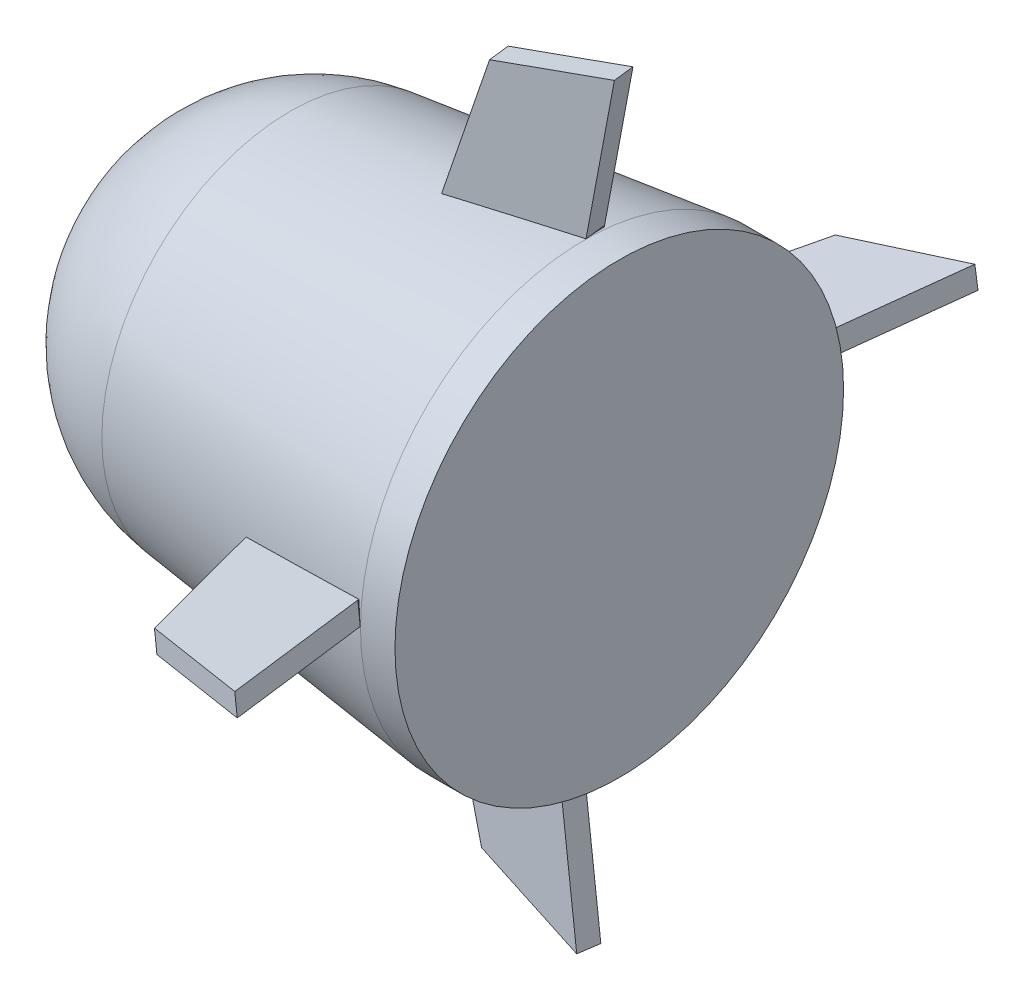
SolidWorks part; units mm, degrees
material "7075-T6 (SN)"
ref_plane "Front Plane" through (0, 0, 0) normal (0, 0, 1) x (1, 0, 0)
ref_plane "Top Plane" through (0, 0, 0) normal (0, 1, 0) x (1, 0, 0)
ref_plane "Right Plane" through (0, 0, 0) normal (1, 0, 0) x (0, 0, -1)
sketch "Sketch1" plane through (0, 0, 0) normal (0, 0, 1) x (1, 0, 0)
  line L1 (68.3553, -5.5711) -> (68.3553, 36.0939)
  line L2 (68.3553, 36.0939) -> (13.6561, 29.4289)
  line L4 (-16.6447, -5.5711) -> (-16.6447, -5.3701)
  line L5 (-16.6447, -5.5711) -> (68.3553, -5.5711)
  arc A0 (13.6561, 29.4289) -> (-16.6447, -5.3701) centre (17.7549, -4.7315) ccw
  dimension "D1" = 85
  dimension "D2" = 41.665
  dimension "D3" = 35
revolve "Revolve1" add sketch "Sketch1" angle 360 about L5
ref_plane "Plane1" through (-4.6714, -38.3379, 0) normal (-0.121, -0.9927, 0) x (-0.9927, 0.121, 0)
sketch "Sketch2" plane through (-4.6714, -38.3379, 0) normal (-0.121, -0.9927, 0) x (-0.9927, 0.121, 0)
  line L0 (0, 0) -> (-73.5668, 0)
  line L1 (-73.5668, 0) -> (-49.7405, 3.134)
  line L2 (-49.7405, 3.134) -> (-49.1838, -1.0985)
  line L3 (-49.1838, -1.0985) -> (-73.0101, -4.2325)
  line L4 (-73.0101, -4.2325) -> (-73.5668, 0)
  ellipse E0 centre (-68.5273, 0) end of major axis (-68.5273, -41.665) minor radius 5.0395 construction
  dimension "D1" = 7.493
ref_plane "Plane2" through (0.6894, -0.084, -5.2796) normal (0.1295, -0.0158, -0.9915) x (0.9842, -0.1199, 0.1304)
sketch "Sketch3" plane through (0.6894, -0.084, -5.2796) normal (0.1295, -0.0158, -0.9915) x (0.9842, -0.1199, 0.1304)
  line L0 (48.907, 38.6214) -> (59.4163, 62.0482)
  line L1 (59.4163, 62.0482) -> (80.5363, 65.0377)
  line L2 (80.5363, 65.0377) -> (72.9385, 38.6214)
  line L3 (72.9385, 38.6214) -> (48.907, 38.6214)
extrude "Boss-Extrude1" add sketch "Sketch3" along normal blind 4 separate body
ref_plane "Plane3" through (-4.6714, -38.3379, 0) normal (0.121, 0.9927, 0) x (0.9927, -0.121, 0)
sketch "Sketch12" plane through (-4.6714, -38.3379, 0) normal (0.121, 0.9927, 0) x (0.9927, -0.121, 0)
  line L0 (49.1838, -1.0985) -> (73.0101, -4.2325)
  line L1 (73.0101, -4.2325) -> (73.5317, -0.2667)
  line L2 (73.5317, -0.2667) -> (49.7054, 2.8673)
  line L3 (49.7054, 2.8673) -> (73.5317, -0.2667) construction
  line L4 (49.7054, 2.8673) -> (49.1838, -1.0985)
extrude "Boss-Extrude5" add sketch "Sketch12" along normal blind 0.5 contours L4 L0 L1 L2
pattern_circular "CirPattern27" count 2 over 360 about axis through (0, -5.5711, 0) along (1, 0, 0) of "Boss-Extrude1", "Boss-Extrude5"
pattern_circular "CirPattern28" count 2 over 270 about axis through (0, -5.5711, 0) along (1, 0, 0) of "Boss-Extrude1", "Boss-Extrude5"
ref_plane "Plane4" through (-3.9926, 0.4865, -32.7632) normal (-0.121, 0.0147, -0.9925) x (-0.9927, -0.002, 0.1209)
sketch "Sketch14" plane through (-3.9926, 0.4865, -32.7632) normal (-0.121, 0.0147, -0.9925) x (-0.9927, -0.002, 0.1209)
  line L0 (0, 0) -> (-72.8525, -1.0289)
  ellipse E0 centre (-67.8424, -5.5832) end of major axis (-67.8502, 36.0817) minor radius 5.0395 construction
mirror "Mirror5" about plane through (0, 0, 0) normal (0, 0, 1) of "CirPattern28", "Boss-Extrude1", "Boss-Extrude5"
ref_plane "Plane5" through (1.2072, -0.1471, -9.2454) normal (0.1295, -0.0158, -0.9915) x (-0.9916, -0.0021, -0.1294)
sketch "Sketch19" plane through (1.2072, -0.1471, -9.2454) normal (0.1295, -0.0158, -0.9915) x (-0.9916, -0.0021, -0.1294)
  line L0 (-67.6792, -47.2353) -> (-71.9959, -74.3814)
  line L1 (-71.9959, -74.3814) -> (-48.207, -72.1348)
  line L2 (-48.207, -72.1348) -> (-43.8273, -44.3021)
  line L3 (-43.8273, -44.3021) -> (-67.6792, -47.2353)
extrude "Cut-Extrude1" cut sketch "Sketch19" along normal blind 7.5 contours L3 L0 L1 L2
ref_plane "Plane8" through (0.6894, -0.084, -5.2796) normal (-0.1295, 0.0158, 0.9915) x (0.9916, 0.0021, 0.1294)
sketch "Sketch25" plane through (0.6894, -0.084, -5.2796) normal (-0.1295, 0.0158, 0.9915) x (0.9916, 0.0021, 0.1294)
  line L0 (50.8912, -68.6997) -> (71.9959, -74.3814)
  line L1 (71.9959, -74.3814) -> (51.3986, -68.8364) construction
  line L2 (71.9959, -74.3814) -> (67.7459, -47.0271)
  line L3 (67.7459, -47.0271) -> (43.8273, -44.3021)
  line L4 (43.8273, -44.3021) -> (50.8912, -68.6997)
  ellipse E0 centre (2180.0534, -5.7378) end of major axis (4472.8952, -5.9139) minor radius 106.5738 (41.4575, 32.8548) -> (58.4264, 34.8346) ccw construction
extrude "Cut-Extrude5" cut sketch "Sketch25" along normal blind 7.5
sketch "Sketch26" plane through (0.6894, -0.084, -5.2796) normal (-0.1295, 0.0158, 0.9915) x (0.9916, 0.0021, 0.1294)
  line L0 (43.8273, -44.3021) -> (43.3255, -44.2404)
  line L1 (43.8273, -44.3021) -> (67.6792, -47.2353) construction
  line L2 (43.8292, -44.2867) -> (43.8273, -44.3021) construction
  line L3 (-4.714, -38.3327) -> (67.6792, -47.2353) construction
  line L4 (43.3255, -44.2404) -> (50.9975, -68.787)
  line L5 (50.9975, -68.787) -> (51.3986, -68.8364)
  line L6 (51.3986, -68.8364) -> (43.8273, -44.3021)
ref_plane "Plane9" through (27.3012, 8.5546, 3.4286) normal (-0.9475, -0.2969, -0.119) x (-0.1138, -0.0346, 0.9929)
sketch "Sketch27" plane through (27.3012, 8.5546, 3.4286) normal (-0.9475, -0.2969, -0.119) x (-0.1138, -0.0346, 0.9929)
  line L0 (-1.0471, -81.1001) -> (-2.4019, -55.4599)
  line L1 (-1.0471, -81.1001) -> (-2.4019, -55.4599) construction
  line L2 (-6.2768, 17.8706) -> (-4.3585, -18.4326) construction
  line L3 (-2.4019, -55.4599) -> (-6.4014, -55.575)
  line L4 (-9.5869, 4.708) -> (-9.0373, -5.6921) construction
  line L5 (-6.4014, -55.575) -> (-5.0415, -81.3112)
  line L6 (-5.0415, -81.3112) -> (-3.5339, -81.2315)
  line L7 (-3.5339, -81.2315) -> (-1.0471, -81.1001)
  ellipse E0 centre (-6.0553, -19.455) end of major axis (-45.7202, -18.1357) minor radius 36.1199 (-6.4014, -55.575) -> (-4.6545, -55.5638) ccw construction
extrude "Cut-Extrude8" cut sketch "Sketch27" along normal blind 7.5 contours L7 L0 L3 L5 L6
ref_plane "Plane11" through (-13.6857, -51.3056, -0.9707) normal (-0.2577, -0.9661, -0.0183) x (-0.9662, 0.2576, 0.0048)
sketch "Sketch28" plane through (-13.6857, -51.3056, -0.9707) normal (-0.2577, -0.9661, -0.0183) x (-0.9662, 0.2576, 0.0048)
  line L0 (-89.2834, -2.6569) -> (-88.7692, -6.6238)
  line L1 (3.9115, 9.9385) -> (-6.4093, 8.5436) construction
  line L2 (17.3, 7.7116) -> (-18.7264, 2.8426) construction
  line L3 (-89.3049, -2.6598) -> (-88.7692, -6.6238) construction
  line L4 (-88.7692, -6.6238) -> (-66.0156, -3.5486)
  line L5 (-54.0653, -1.9335) -> (-77.6452, -5.1204) construction
  line L6 (-66.0156, -3.5486) -> (-66.5514, 0.4154)
  line L7 (-66.5514, 0.4154) -> (-89.2834, -2.6569)
extrude "Cut-Extrude9" cut sketch "Sketch28" along normal blind 7.5
ref_plane "Plane14" through (68.3553, 0, 0) normal (1, 0, 0) x (0, 0, -1)
sketch "Sketch33" plane through (68.3553, 0, 0) normal (1, 0, 0) x (0, 0, -1)
  line L0 (2.6971, -47.3951) -> (2.6893, -47.5339)
  line L1 (1.4968, -68.8649) -> (2.8673, -44.3499) construction
  line L2 (2.6893, -47.5339) -> (4.2649, -47.5339)
  line L3 (4.2649, -47.5339) -> (4.3158, -47.2752)
  line L4 (4.3158, -47.2752) -> (2.6971, -47.3951)
  circle A0 centre (34.6745, -29.0713) radius 0.1122
  circle A1 centre (4.2649, -47.5339) radius 1.5646
scale "Scale1" scale about centroid uniform scaling yes scale factor 0.78
sketch "Sketch34" plane through (60.8284, 0, 0) normal (1, 0, 0) x (0, 0, -1)
  circle A0 centre (0, -5.5674) radius 32.76
sketch "Sketch35" plane through (60.8284, 0, 0) normal (1, 0, 0) x (0, 0, -1)
  circle A0 centre (0, -5.5674) radius 32.4987
extrude "Boss-Extrude6" add sketch "Sketch35" along normal blind 5
